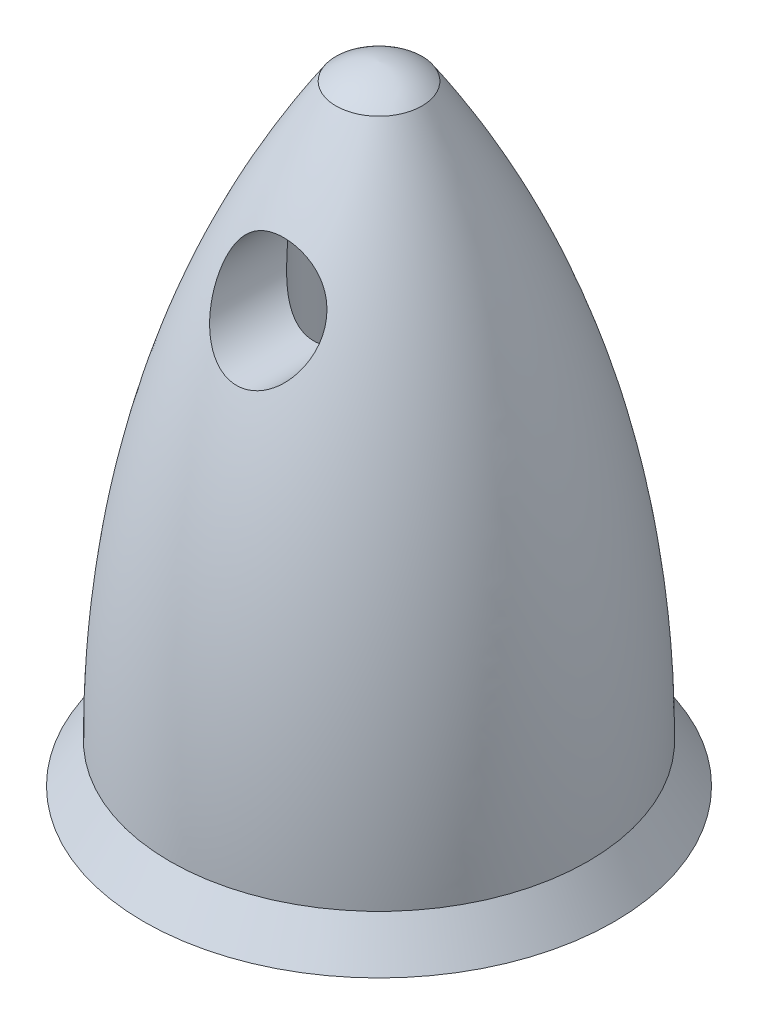
SolidWorks part; units mm, degrees
ref_plane "Front Plane" through (0, 0, 0) normal (0, 0, 1) x (1, 0, 0)
ref_plane "Top Plane" through (0, 0, 0) normal (0, 1, 0) x (1, 0, 0)
ref_plane "Right Plane" through (0, 0, 0) normal (1, 0, 0) x (0, 0, -1)
sketch "Sketch2" plane through (0, 0, 0) normal (0, 0, 1) x (1, 0, 0)
  line L0 (0, 0) -> (9, 0)
  line L1 (0, 0) -> (0, 8.2394) construction
  line L2 (0, 1.5) -> (8, 1.5)
  line L3 (8, 1.5) -> (9, 0)
  line L4 (0, 0) -> (0, 1.5)
  line L5 (0, 1.5) -> (0, 24)
  line L6 (8, 1.5) -> (8.0051, 13.8195) construction
  line L7 (8.0051, 13.8195) -> (1.6474, 23.3622) construction
  spline S0 degree 2 poles (8, 1.5) (8.0051, 13.8195) (1.6474, 23.3622) knots 0 0 0 1 1 1
  spline S1 degree 2 poles (1.6474, 23.3622) (0.9283, 23.94) (0, 24) knots 0 0 0 1 1 1
  point P10 (1.8785, 23.1636)
  point P11 (1.6474, 23.3622)
  point P12 (8.0051, 13.8195)
  dimension "D1" = 18
  dimension "D2" = 16
  dimension "D3" = 1.5
  dimension "D4" = 24
revolve "Revolve1" add sketch "Sketch2" angle 360 about L1
sketch "Sketch3" plane through (0, 0, 0) normal (0, -1, 0) x (1, 0, 0)
  circle A0 centre (0, 0) radius 2.5
  dimension "D1" = 5
extrude "Cut-Extrude1" cut sketch "Sketch3" against normal blind 21
chamfer "Chamfer1" distance 0.5 angle 45 1 edges at (0, 0, -2.5)
sketch "Sketch4" plane through (0, 0, 0) normal (0, 0, 1) x (1, 0, 0)
  line L0 (0, 0) -> (0, 24) construction
  circle A0 centre (0, 18) radius 2
  dimension "D1" = 4
  dimension "D2" = 18
extrude "Cut-Extrude2" cut sketch "Sketch4" against normal through all and the other way through all
